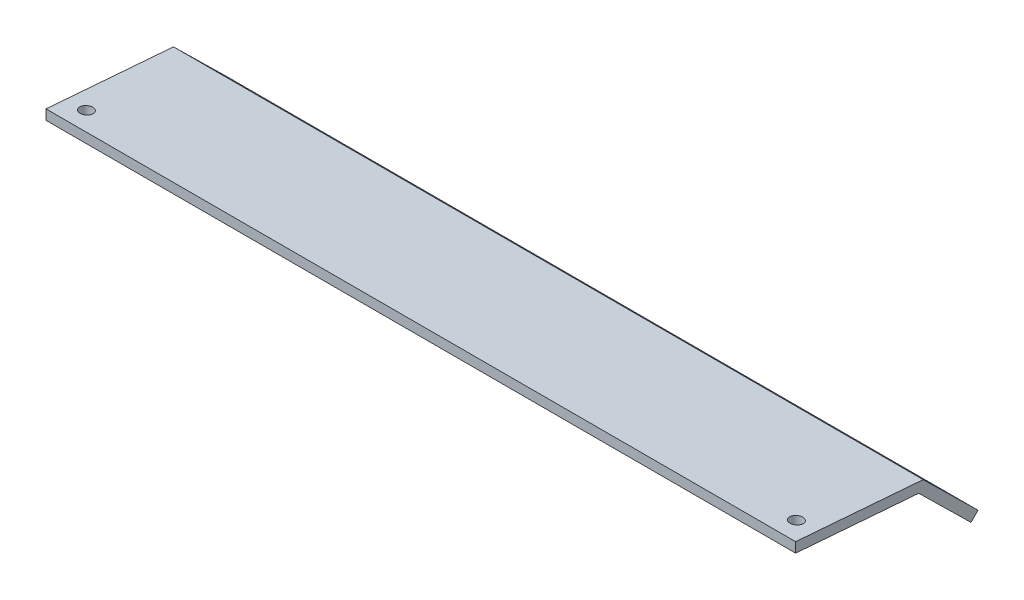
SolidWorks part; units mm, degrees
ref_plane "Front Plane" through (0, 0, 0) normal (0, 0, 1) x (1, 0, 0)
ref_plane "Top Plane" through (0, 0, 0) normal (0, 1, 0) x (1, 0, 0)
ref_plane "Right Plane" through (0, 0, 0) normal (1, 0, 0) x (0, 0, -1)
sketch "Sketch1" plane through (0, 0, 0) normal (1, 0, 0) x (0, 0, -1)
  line L7 (39.3618, -3.0969) -> (56.0795, -19.5255) construction
  line L8 (0, 0) -> (0, 3.1848)
  line L9 (0, 3.1848) -> (40.7629, -0.0223)
  line L10 (40.7629, -0.0223) -> (58.3049, -17.2609)
  line L11 (58.3049, -17.2609) -> (56.0795, -19.5255)
  line L12 (56.0795, -19.5255) -> (39.3618, -3.0969)
  line L13 (39.3618, -3.0969) -> (0, 0)
  arc A0 (56.0826, -21.3341) -> (56.1064, -19.5527) centre (55.1893, -20.4313) ccw construction
  arc A1 (56.0826, -21.3341) -> (56.0795, -19.5255) centre (55.1893, -20.4313) ccw construction
  dimension "D1" = 3.175
  dimension "D2" = 3.175
extrude "Boss-Extrude1" add sketch "Sketch1" along normal mid plane 239.7125
sketch "Sketch2" plane through (0, 3.1652, -0.249) normal (0, 0.9969, -0.0784) x (1, 0, 0)
  circle A0 centre (113.5062, 6.3549) radius 2.032
  circle A1 centre (-113.5063, 6.3549) radius 2.032
  dimension "D1" = 4.064
extrude "Cut-Extrude1" cut sketch "Sketch2" against normal through all
sketch "Sketch3" plane through (0, 20.367, -20.0148) normal (0, 0.7132, -0.7009) x (1, 0, 0)
  circle A0 centre (-113.5062, 45.4292) radius 2.032
  circle A1 centre (113.5063, 48.6042) radius 2.032
  dimension "D1" = 4.064
extrude "Cut-Extrude2" cut sketch "Sketch3" against normal blind 12.7
